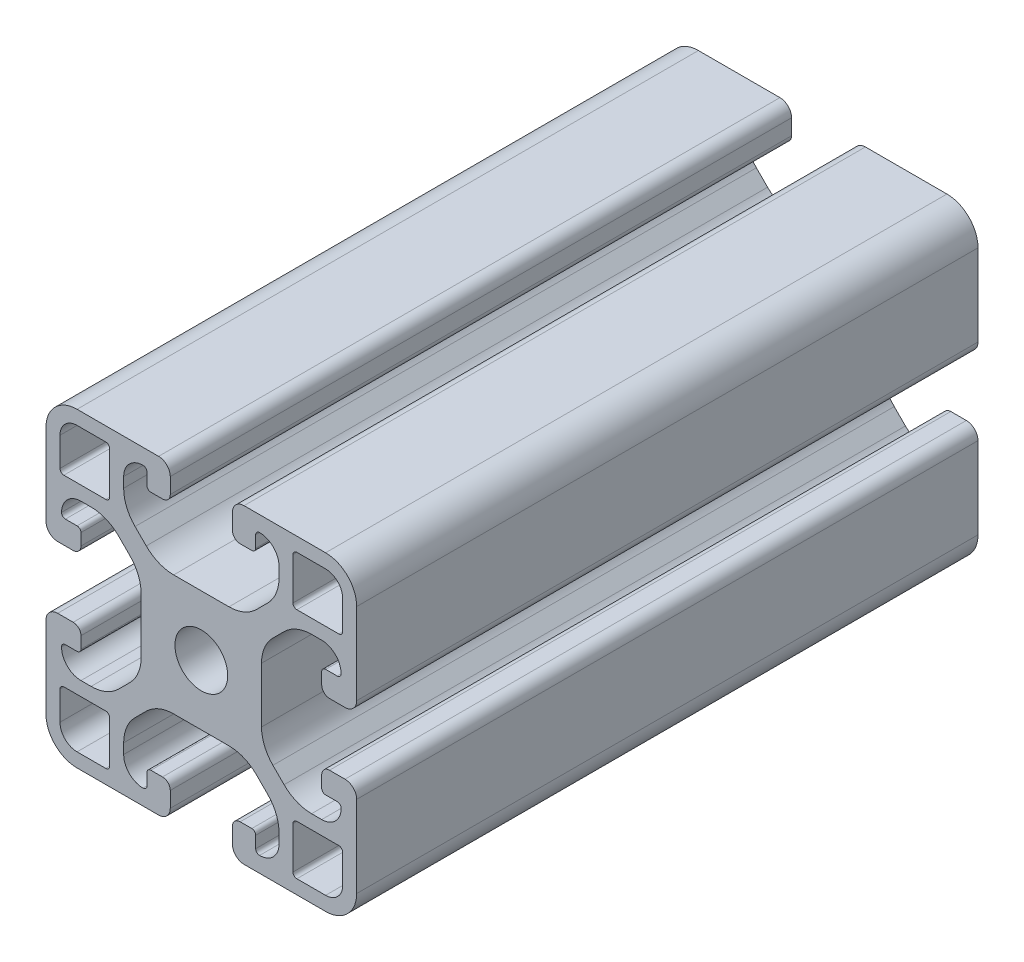
SolidWorks part; units mm, degrees
ref_plane "Plan de face" through (0, 0, 0) normal (0, 0, 1) x (1, 0, 0)
ref_plane "Plan de dessus" through (0, 0, 0) normal (0, 1, 0) x (1, 0, 0)
ref_plane "Plan de droite" through (0, 0, 0) normal (1, 0, 0) x (0, 0, -1)
ref_plane "Plan1" through (0, 0, -30) normal (0, 0, -1) x (-1, 0, 0)
sketch "Esquisse1" plane through (0, 0, -30) normal (0, 0, -1) x (-1, 0, 0)
  line B0 (-4.5, 15) -> (-4.5, 13.5)
  line B1 (-4, 13) -> (-2.5, 13)
  line B2 (-4.5, 10) -> (-5.8076, 10)
  line B3 (-9.3431, 11.4645) -> (-10.7855, 12.9069)
  line B4 (-12.25, 16.4424) -> (-12.25, 23.5576)
  line B5 (-10.7855, 27.0931) -> (-9.3431, 28.5355)
  line B6 (-5.8076, 30) -> (-4.5, 30)
  line B7 (-2.5, 27) -> (-4, 27)
  line B8 (-4.5, 26.5) -> (-4.5, 25)
  line B9 (-3.5, 24) -> (-1.5, 24)
  line B10 (0, 25.5) -> (0, 36)
  line B11 (-4, 40) -> (-14.5, 40)
  line B12 (-16, 38.5) -> (-16, 36.5)
  line B13 (-15, 35.5) -> (-13.5, 35.5)
  line B14 (-13, 36) -> (-13, 37.5)
  line B15 (-10, 35.5) -> (-10, 34.1924)
  line B16 (-11.4645, 30.6569) -> (-12.9069, 29.2145)
  line B17 (-16.4424, 27.75) -> (-23.5576, 27.75)
  line B18 (-27.0931, 29.2145) -> (-28.5355, 30.6569)
  line B19 (-30, 34.1924) -> (-30, 35.5)
  line B20 (-27, 37.5) -> (-27, 36)
  line B21 (-26.5, 35.5) -> (-25, 35.5)
  line B22 (-24, 36.5) -> (-24, 38.5)
  line B23 (-25.5, 40) -> (-36, 40)
  line B24 (-40, 36) -> (-40, 25.5)
  line B25 (-38.5, 24) -> (-36.5, 24)
  line B26 (-35.5, 25) -> (-35.5, 26.5)
  line B27 (-36, 27) -> (-37.5, 27)
  line B28 (-35.5, 30) -> (-34.1924, 30)
  line B29 (-30.6569, 28.5355) -> (-29.2145, 27.0931)
  line B30 (-27.75, 23.5576) -> (-27.75, 16.4424)
  line B31 (-29.2145, 12.9069) -> (-30.6569, 11.4645)
  line B32 (-34.1924, 10) -> (-35.5, 10)
  line B33 (-37.5, 13) -> (-36, 13)
  line B34 (-35.5, 13.5) -> (-35.5, 15)
  line B35 (-36.5, 16) -> (-38.5, 16)
  line B36 (-40, 14.5) -> (-40, 4)
  line B37 (-36, 0) -> (-25.5, 0)
  line B38 (-24, 1.5) -> (-24, 3.5)
  line B39 (-25, 4.5) -> (-26.5, 4.5)
  line B40 (-27, 4) -> (-27, 2.5)
  line B41 (-30, 4.5) -> (-30, 5.8076)
  line B42 (-28.5355, 9.3431) -> (-27.0931, 10.7855)
  line B43 (-23.5576, 12.25) -> (-16.4424, 12.25)
  line B44 (-12.9069, 10.7855) -> (-11.4645, 9.3431)
  line B45 (-10, 5.8076) -> (-10, 4.5)
  line B46 (-13, 2.5) -> (-13, 4)
  line B47 (-13.5, 4.5) -> (-15, 4.5)
  line B48 (-16, 3.5) -> (-16, 1.5)
  line B49 (-14.5, 0) -> (-4, 0)
  line B50 (0, 4) -> (0, 14.5)
  line B51 (-1.5, 16) -> (-3.5, 16)
  line B52 (-4, 1.8) -> (-7.7, 1.8)
  line B53 (-8.2, 2.3) -> (-8.2, 7.7)
  line B54 (-7.7, 8.2) -> (-2.3, 8.2)
  line B55 (-1.8, 7.7) -> (-1.8, 4)
  line B56 (-38.2, 4) -> (-38.2, 7.7)
  line B57 (-37.7, 8.2) -> (-32.3, 8.2)
  line B58 (-31.8, 7.7) -> (-31.8, 2.3)
  line B59 (-32.3, 1.8) -> (-36, 1.8)
  line B60 (-36, 38.2) -> (-32.3, 38.2)
  line B61 (-31.8, 37.7) -> (-31.8, 32.3)
  line B62 (-32.3, 31.8) -> (-37.7, 31.8)
  line B63 (-38.2, 32.3) -> (-38.2, 36)
  line B64 (-1.8, 36) -> (-1.8, 32.3)
  line B65 (-2.3, 31.8) -> (-7.7, 31.8)
  line B66 (-8.2, 32.3) -> (-8.2, 37.7)
  line B67 (-7.7, 38.2) -> (-4, 38.2)
  arc B68 (-4.5, 13.5) -> (-4, 13) centre (-4, 13.5) ccw
  arc B69 (-2.5, 13) -> (-2, 12.5) centre (-2.5, 12.5) cw
  arc B70 (-2, 12.5) -> (-4.5, 10) centre (-4.5, 12.5) cw
  arc B71 (-5.8076, 10) -> (-9.3431, 11.4645) centre (-5.8076, 15) cw
  arc B72 (-10.7855, 12.9069) -> (-12.25, 16.4424) centre (-7.25, 16.4424) cw
  arc B73 (-12.25, 23.5576) -> (-10.7855, 27.0931) centre (-7.25, 23.5576) cw
  arc B74 (-9.3431, 28.5355) -> (-5.8076, 30) centre (-5.8076, 25) cw
  arc B75 (-4.5, 30) -> (-2, 27.5) centre (-4.5, 27.5) cw
  arc B76 (-2, 27.5) -> (-2.5, 27) centre (-2.5, 27.5) cw
  arc B77 (-4, 27) -> (-4.5, 26.5) centre (-4, 26.5) ccw
  arc B78 (-4.5, 25) -> (-3.5, 24) centre (-3.5, 25) ccw
  arc B79 (-1.5, 24) -> (0, 25.5) centre (-1.5, 25.5) ccw
  arc B80 (0, 36) -> (-4, 40) centre (-4, 36) ccw
  arc B81 (-14.5, 40) -> (-16, 38.5) centre (-14.5, 38.5) ccw
  arc B82 (-16, 36.5) -> (-15, 35.5) centre (-15, 36.5) ccw
  arc B83 (-13.5, 35.5) -> (-13, 36) centre (-13.5, 36) ccw
  arc B84 (-13, 37.5) -> (-12.5, 38) centre (-12.5, 37.5) cw
  arc B85 (-12.5, 38) -> (-10, 35.5) centre (-12.5, 35.5) cw
  arc B86 (-10, 34.1924) -> (-11.4645, 30.6569) centre (-15, 34.1924) cw
  arc B87 (-12.9069, 29.2145) -> (-16.4424, 27.75) centre (-16.4424, 32.75) cw
  arc B88 (-23.5576, 27.75) -> (-27.0931, 29.2145) centre (-23.5576, 32.75) cw
  arc B89 (-28.5355, 30.6569) -> (-30, 34.1924) centre (-25, 34.1924) cw
  arc B90 (-30, 35.5) -> (-27.5, 38) centre (-27.5, 35.5) cw
  arc B91 (-27.5, 38) -> (-27, 37.5) centre (-27.5, 37.5) cw
  arc B92 (-27, 36) -> (-26.5, 35.5) centre (-26.5, 36) ccw
  arc B93 (-25, 35.5) -> (-24, 36.5) centre (-25, 36.5) ccw
  arc B94 (-24, 38.5) -> (-25.5, 40) centre (-25.5, 38.5) ccw
  arc B95 (-36, 40) -> (-40, 36) centre (-36, 36) ccw
  arc B96 (-40, 25.5) -> (-38.5, 24) centre (-38.5, 25.5) ccw
  arc B97 (-36.5, 24) -> (-35.5, 25) centre (-36.5, 25) ccw
  arc B98 (-35.5, 26.5) -> (-36, 27) centre (-36, 26.5) ccw
  arc B99 (-37.5, 27) -> (-38, 27.5) centre (-37.5, 27.5) cw
  arc B100 (-38, 27.5) -> (-35.5, 30) centre (-35.5, 27.5) cw
  arc B101 (-34.1924, 30) -> (-30.6569, 28.5355) centre (-34.1924, 25) cw
  arc B102 (-29.2145, 27.0931) -> (-27.75, 23.5576) centre (-32.75, 23.5576) cw
  arc B103 (-27.75, 16.4424) -> (-29.2145, 12.9069) centre (-32.75, 16.4424) cw
  arc B104 (-30.6569, 11.4645) -> (-34.1924, 10) centre (-34.1924, 15) cw
  arc B105 (-35.5, 10) -> (-38, 12.5) centre (-35.5, 12.5) cw
  arc B106 (-38, 12.5) -> (-37.5, 13) centre (-37.5, 12.5) cw
  arc B107 (-36, 13) -> (-35.5, 13.5) centre (-36, 13.5) ccw
  arc B108 (-35.5, 15) -> (-36.5, 16) centre (-36.5, 15) ccw
  arc B109 (-38.5, 16) -> (-40, 14.5) centre (-38.5, 14.5) ccw
  arc B110 (-40, 4) -> (-36, 0) centre (-36, 4) ccw
  arc B111 (-25.5, 0) -> (-24, 1.5) centre (-25.5, 1.5) ccw
  arc B112 (-24, 3.5) -> (-25, 4.5) centre (-25, 3.5) ccw
  arc B113 (-26.5, 4.5) -> (-27, 4) centre (-26.5, 4) ccw
  arc B114 (-27, 2.5) -> (-27.5, 2) centre (-27.5, 2.5) cw
  arc B115 (-27.5, 2) -> (-30, 4.5) centre (-27.5, 4.5) cw
  arc B116 (-30, 5.8076) -> (-28.5355, 9.3431) centre (-25, 5.8076) cw
  arc B117 (-27.0931, 10.7855) -> (-23.5576, 12.25) centre (-23.5576, 7.25) cw
  arc B118 (-16.4424, 12.25) -> (-12.9069, 10.7855) centre (-16.4424, 7.25) cw
  arc B119 (-11.4645, 9.3431) -> (-10, 5.8076) centre (-15, 5.8076) cw
  arc B120 (-10, 4.5) -> (-12.5, 2) centre (-12.5, 4.5) cw
  arc B121 (-12.5, 2) -> (-13, 2.5) centre (-12.5, 2.5) cw
  arc B122 (-13, 4) -> (-13.5, 4.5) centre (-13.5, 4) ccw
  arc B123 (-15, 4.5) -> (-16, 3.5) centre (-15, 3.5) ccw
  arc B124 (-16, 1.5) -> (-14.5, 0) centre (-14.5, 1.5) ccw
  arc B125 (-4, 0) -> (0, 4) centre (-4, 4) ccw
  arc B126 (0, 14.5) -> (-1.5, 16) centre (-1.5, 14.5) ccw
  arc B127 (-3.5, 16) -> (-4.5, 15) centre (-3.5, 15) ccw
  circle B128 centre (-20, 20) radius 3.4
  arc B129 (-1.8, 4) -> (-4, 1.8) centre (-4, 4) cw
  arc B130 (-7.7, 1.8) -> (-8.2, 2.3) centre (-7.7, 2.3) cw
  arc B131 (-8.2, 7.7) -> (-7.7, 8.2) centre (-7.7, 7.7) cw
  arc B132 (-2.3, 8.2) -> (-1.8, 7.7) centre (-2.3, 7.7) cw
  arc B133 (-36, 1.8) -> (-38.2, 4) centre (-36, 4) cw
  arc B134 (-38.2, 7.7) -> (-37.7, 8.2) centre (-37.7, 7.7) cw
  arc B135 (-32.3, 8.2) -> (-31.8, 7.7) centre (-32.3, 7.7) cw
  arc B136 (-31.8, 2.3) -> (-32.3, 1.8) centre (-32.3, 2.3) cw
  arc B137 (-38.2, 36) -> (-36, 38.2) centre (-36, 36) cw
  arc B138 (-32.3, 38.2) -> (-31.8, 37.7) centre (-32.3, 37.7) cw
  arc B139 (-31.8, 32.3) -> (-32.3, 31.8) centre (-32.3, 32.3) cw
  arc B140 (-37.7, 31.8) -> (-38.2, 32.3) centre (-37.7, 32.3) cw
  arc B141 (-4, 38.2) -> (-1.8, 36) centre (-4, 36) cw
  arc B142 (-1.8, 32.3) -> (-2.3, 31.8) centre (-2.3, 32.3) cw
  arc B143 (-7.7, 31.8) -> (-8.2, 32.3) centre (-7.7, 32.3) cw
  arc B144 (-8.2, 37.7) -> (-7.7, 38.2) centre (-7.7, 37.7) cw
sketch_block_instance "Bloc1-1"
sketch_block "Bloc1"
extrude "Boss.-Extru.1" add sketch "Esquisse1" against normal blind 80
